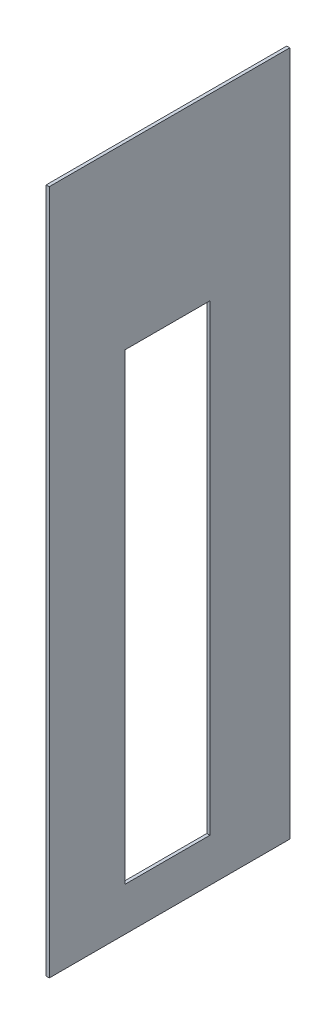
SolidWorks part; units mm, degrees
ref_plane "Спереди" through (0, 0, 0) normal (0, 0, 1) x (1, 0, 0)
ref_plane "Сверху" through (0, 0, 0) normal (0, 1, 0) x (1, 0, 0)
ref_plane "Справа" through (0, 0, 0) normal (1, 0, 0) x (0, 0, -1)
ref_plane "Плоскость4" through (0.5, 0, 0) normal (-1, 0, 0) x (0, -1, 0)
sketch "Эскиз1" plane through (0.5, 0, 0) normal (-1, 0, 0) x (0, -1, 0)
  line L0 (9.85, 42.25) -> (-100.85, 42.25)
  line L1 (-100.85, 42.25) -> (-100.85, 3.4)
  line L2 (-100.85, 3.4) -> (9.85, 3.4)
  line L3 (9.85, 3.4) -> (9.85, 42.25)
extrude "Бобышка-Вытянуть1" add sketch "Эскиз1" against normal blind 0.5
sketch "Эскиз3" plane through (0.5, 0, 0) normal (-1, 0, 0) x (0, 0, 1)
  line L1 (30.0066, -2.8534) -> (16.3037, -2.8534)
  line L2 (30.0066, -2.8534) -> (30.0066, 71.9075)
  line L3 (30.0066, 71.9075) -> (16.3037, 71.9075)
  line L4 (16.3037, -2.8534) -> (16.3037, 71.9075)
extrude "Вырез-Вытянуть1" cut sketch "Эскиз3" against normal through all
